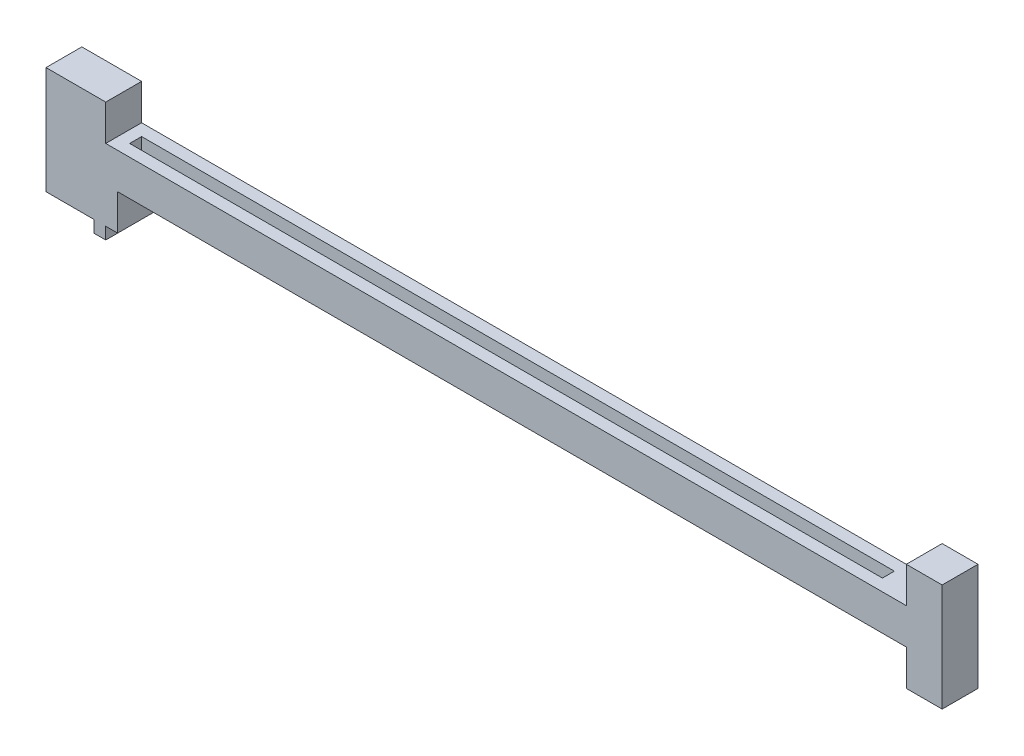
SolidWorks part; units mm, degrees
ref_plane "Front Plane" through (0, 0, 0) normal (0, 0, 1) x (1, 0, 0)
ref_plane "Top Plane" through (0, 0, 0) normal (0, 1, 0) x (1, 0, 0)
ref_plane "Right Plane" through (0, 0, 0) normal (1, 0, 0) x (0, 0, -1)
sketch "Sketch1" plane through (0, 0, 0) normal (0, 0, 1) x (1, 0, 0)
  line L0 (-55, 7.5) -> (-55, 2.5)
  line L1 (-60, 7.5) -> (-55, 7.5)
  line L2 (-60, 7.5) -> (-60, -7.5)
  line L3 (-60, -7.5) -> (-55, -7.5)
  line L4 (60, 7.5) -> (60, -7.5)
  line L5 (55, 7.5) -> (55, 2.5)
  line L6 (55, -7.5) -> (60, -7.5)
  line L7 (-55, 2.5) -> (55, 2.5)
  line L9 (-55, -2.5) -> (55, -2.5)
  line L11 (55, 7.5) -> (60, 7.5)
  line L12 (-55, -2.5) -> (-55, -7.5)
  line L13 (55, -2.5) -> (55, -7.5)
  line L14 (-60, 7.5) -> (60, -7.5) construction
  line L15 (60, 7.5) -> (-60, -7.5) construction
  point P12 (0, 0)
  dimension "D1" = 5
  dimension "D2" = 5
  dimension "D3" = 5
  dimension "D4" = 5
  dimension "D5" = 15
  dimension "D6" = 120
extrude "Slider Main Body" add sketch "Sketch1" along normal blind 5
sketch "Sketch2" plane through (0, -7.5, 0) normal (0, -1, 0) x (1, 0, 0)
  line L0 (-60, 5) -> (-55, 5) construction
  line L1 (-58.3333, 5) -> (-56.6667, 5)
  line L2 (-58.3333, 5) -> (-58.3333, 0)
  line L3 (-58.3333, 0) -> (-56.6667, 0)
  line L4 (-56.6667, 5) -> (-56.6667, 0)
  line L5 (-60, 0) -> (-55, 0) construction
  line L6 (-60, 5) -> (-60, 0) construction
  line L7 (-55, 5) -> (-55, 0) construction
  dimension "D1" = 1.6667
  dimension "D2" = 1.6667
extrude "Track Slider" add sketch "Sketch2" along normal blind 1.6667
sketch "Sketch3" plane through (0, 0, 5) normal (0, 0, 1) x (1, 0, 0)
  line L0 (-60, -7.5) -> (-58.3333, -7.5) construction
  line L1 (-60, 7.5) -> (-65, 7.5)
  line L2 (-60, 7.5) -> (-60, -7.5)
  line L3 (-60, -7.5) -> (-65, -7.5)
  line L4 (-65, 7.5) -> (-65, -7.5)
  dimension "D1" = 5
extrude "Handle" add sketch "Sketch3" against normal up to surface (5 mm away) up to face at (-14.375, -2.0833, 0)
sketch "Sketch4" plane through (0, -2.5, 0) normal (0, -1, 0) x (1, 0, 0)
  line L0 (50, 5) -> (50, 0)
  line L1 (-55, 5) -> (55, 5) construction
  line L2 (-55, 0) -> (55, 0) construction
  line L3 (55, 5) -> (55, 0) construction
  line L4 (-55, 5) -> (-55, 0) construction
  line L5 (-55, 3.3333) -> (50, 3.3333)
  line L6 (-55, 3.3333) -> (-55, 1.6667)
  line L7 (-55, 1.6667) -> (50, 1.6667)
  line L8 (50, 3.3333) -> (50, 1.6667)
  dimension "D1" = 5
  dimension "D2" = 1.6667
  dimension "D3" = 1.6667
extrude "Cut-Extrude1" cut sketch "Sketch4" against normal through all contours L5 L8 L7 L6
sketch "Sketch5" plane through (0, 7.5, 0) normal (0, 1, 0) x (1, 0, 0)
  line L0 (-55, -5) -> (-65, -5) construction
  line L1 (-55, 0) -> (-56.6667, 0)
  line L2 (-55, 0) -> (-55, -5)
  line L3 (-55, -5) -> (-56.6667, -5)
  line L4 (-56.6667, 0) -> (-56.6667, -5)
  line L5 (-55, 0) -> (-56.6667, -5) construction
  line L6 (-55, -5) -> (-56.6667, 0) construction
  point P4 (-55.8333, -2.5)
  dimension "D1" = 1.6667
extrude "Cut-Extrude2" cut sketch "Sketch5" against normal up to surface (5 mm away) up to face at (-1.25, 2.5, 2.5)
equation "\"Frame side length\"= \"Useful Tray Size\" + \"Universal Bar Height\" * 3"
equation "\"Universal Bar Height\"= 5mm"
equation "\"D1@Sketch1\"=\"Universal Bar Height\""
equation "\"D2@Sketch1\"=\"Universal Bar Height\""
equation "\"D3@Sketch1\"=\"Universal Bar Height\""
equation "\"D4@Sketch1\"=\"Universal Bar Height\""
equation "\"D5@Sketch1\"=\"Universal Bar Height\"*3"
equation "\"D6@Sketch1\"=\"Universal Bar Height\"+\"Frame side length\""
equation "\"D1@Slider Main Body\" = \"Universal Bar Height\""
equation "\"D1@Sketch2\"=\"Universal Bar Height\"/3"
equation "\"D2@Sketch2\"=\"Universal Bar Height\"/3"
equation "\"D1@Track Slider\" = \"Universal Bar Height\" / 3"
equation "\"Useful Tray Size\"= 100mm"
equation "\"D1@Sketch3\"=\"Universal Bar Height\""
equation "\"D1@Sketch4\"=\"Universal Bar Height\""
equation "\"D2@Sketch4\"=\"Universal Bar Height\"/3"
equation "\"D3@Sketch4\"=\"Universal Bar Height\"/3"
equation "\"D1@Sketch5\"=\"Universal Bar Height\"/3"
